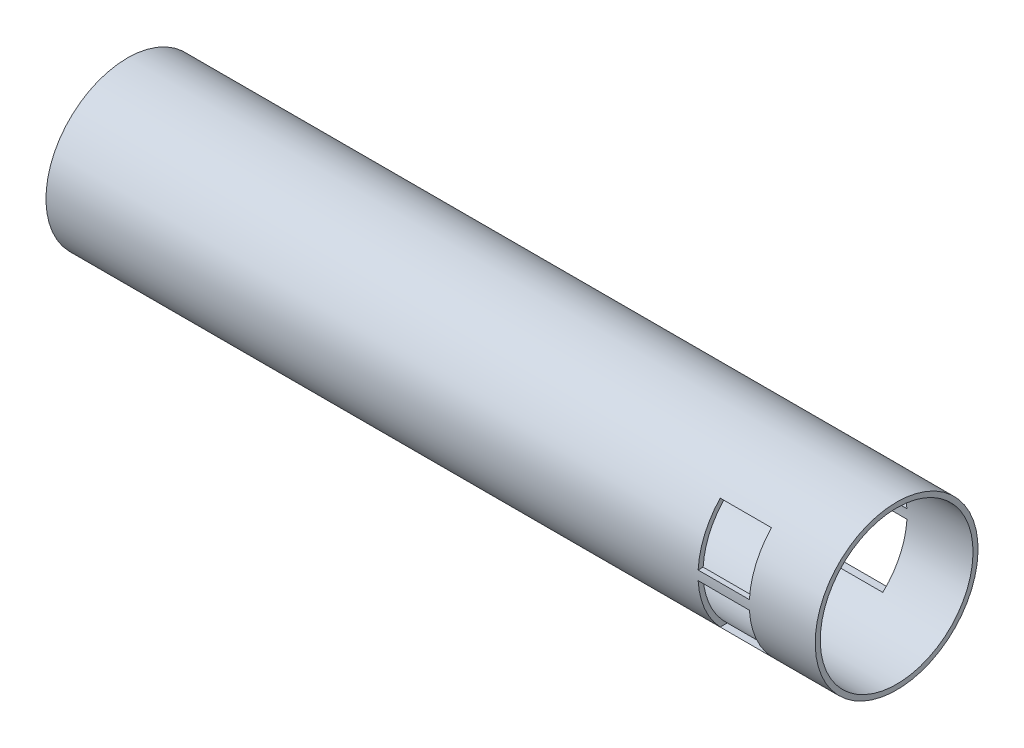
SolidWorks part; units mm, degrees
ref_plane "Front Plane" through (0, 0, 0) normal (0, 0, 1) x (1, 0, 0)
ref_plane "Top Plane" through (0, 0, 0) normal (0, 1, 0) x (1, 0, 0)
ref_plane "Right Plane" through (0, 0, 0) normal (1, 0, 0) x (0, 0, -1)
sketch "Sketch1" plane through (0, 0, 0) normal (0, 0, 1) x (1, 0, 0)
  line L0 (-210, 0) -> (210, 0)
  point P4 (0, 0)
  dimension "D1" = 420
ref_plane "Plane1" through (-210, 0, 0) normal (1, 0, 0) x (0, 1, 0)
other "Pipe 0.5 SCH 40(1)"
ref_plane "Plane2" through (-210, 0, 0) normal (1, 0, 0) x (0, 1, 0)
sketch "Sketch12" plane through (-210, 0, 0) normal (1, 0, 0) x (0, 1, 0)
  circle A0 centre (0, 0) radius 44.45
  circle A1 centre (0, 0) radius 41.7068
  point P0 (0, 0)
  dimension "D1" = 88.9
  dimension "D2" = 83.4136
sketch "Sketch13" plane through (0, 0, 0) normal (0, 0, 1) x (1, 0, 0)
  line L0 (210, 0) -> (160, 0) construction
  line L1 (-210, 0) -> (210, 0) construction
  line L2 (160, 0) -> (160, 16.5) construction
  line L7 (160, 0) -> (160, -16.5) construction
  line L9 (146, 30.5) -> (174, 30.5)
  line L10 (146, 30.5) -> (146, 2.5)
  line L11 (146, 2.5) -> (174, 2.5)
  line L12 (174, 30.5) -> (174, 2.5)
  line L13 (146, 30.5) -> (174, 2.5) construction
  line L14 (146, 2.5) -> (174, 30.5) construction
  line L15 (146, -2.5) -> (174, -2.5)
  line L16 (146, -2.5) -> (146, -30.5)
  line L17 (146, -30.5) -> (174, -30.5)
  line L18 (174, -2.5) -> (174, -30.5)
  line L19 (146, -2.5) -> (174, -30.5) construction
  line L20 (146, -30.5) -> (174, -2.5) construction
  dimension "D1" = 28
  dimension "D2" = 28
  dimension "D3" = 28
  dimension "D4" = 28
  dimension "D5" = 50
  dimension "D6" = 16.5
  dimension "D7" = 16.5
extrude "Cut-Extrude1" cut sketch "Sketch13" against normal blind 50 and the other way blind 50
